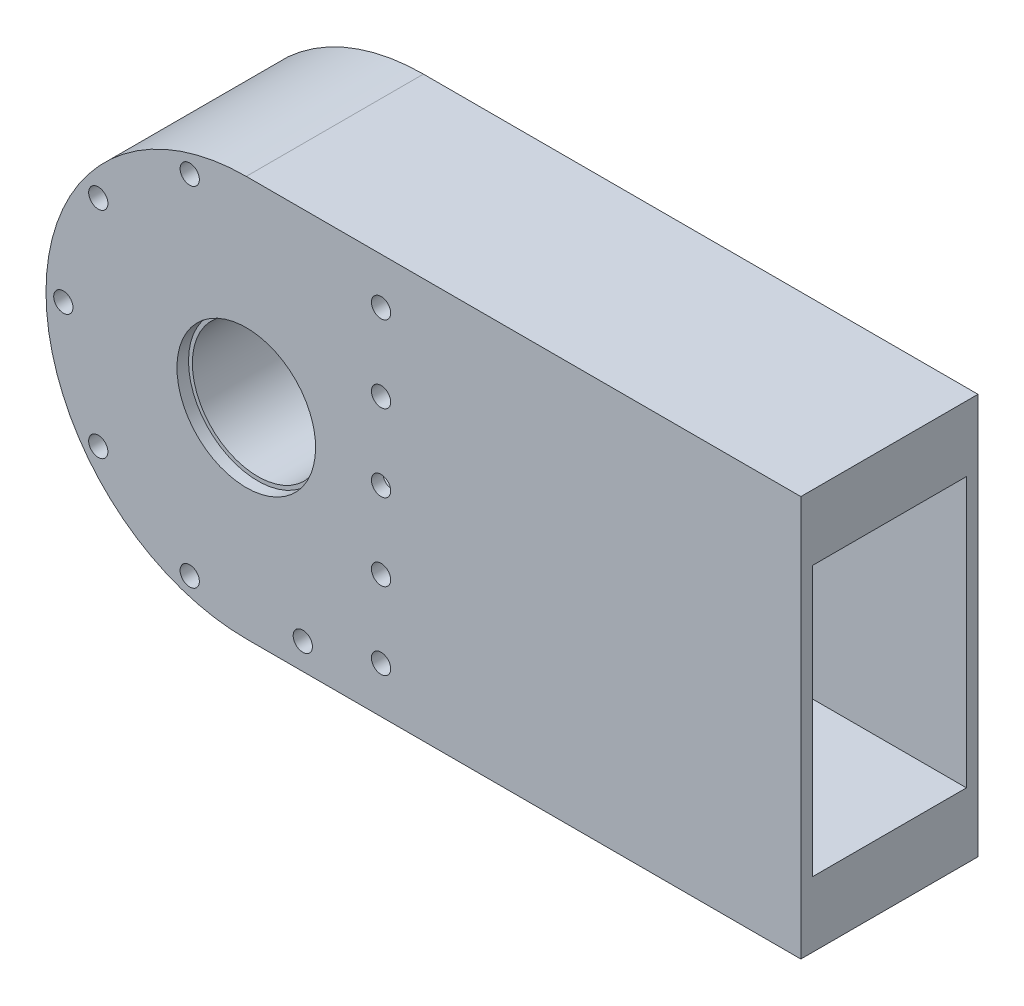
SolidWorks part; units mm, degrees
ref_plane "Alzado" through (0, 0, 0) normal (0, 0, 1) x (1, 0, 0)
ref_plane "Planta" through (0, 0, 0) normal (0, 1, 0) x (1, 0, 0)
ref_plane "Vista lateral" through (0, 0, 0) normal (1, 0, 0) x (0, 0, -1)
sketch "Croquis2" plane through (0, 0, 0) normal (0, 0, 1) x (1, 0, 0)
  line L0 (0, 52) -> (144, 52)
  line L1 (0, -52) -> (144, -52)
  line L2 (144, 52) -> (144, -52)
  line L3 (40, 35) -> (40, -35)
  line L4 (40, -35) -> (144, -35)
  line L5 (40, 35) -> (144, 35)
  line L6 (40, 5) -> (16.2481, 5)
  line L7 (40, -5) -> (16.2481, -5)
  line L8 (28.124, 5) -> (28.124, -5) construction
  arc A0 (0, 52) -> (0, -52) centre (0, 0) ccw
  circle A1 centre (0, 0) radius 17
  point P9 (40, 0)
  dimension "D1" = 104
  dimension "D3" = 34
  dimension "D2" = 144
  dimension "D4" = 70
  dimension "D5" = 40
  dimension "D6" = 10
extrude "Saliente-Extruir1" add sketch "Croquis2" along normal blind 40 contours A1 L6 L3 L5 L2 L0 A0 L1 L4 L7
sketch "Croquis4" plane through (0, 0, 40) normal (0, 0, 1) x (1, 0, 0)
  line L0 (144, 52) -> (144, -52)
  line L10 (16.2481, 5) -> (40, 5)
  line L11 (40, 5) -> (40, 35)
  line L12 (40, 35) -> (144, 35)
  line L13 (144, 35) -> (144, 52)
  line L14 (144, 52) -> (0, 52)
  line L15 (0, -52) -> (144, -52)
  line L16 (144, -52) -> (144, -35)
  line L17 (144, -35) -> (40, -35)
  line L18 (40, -35) -> (40, -5)
  line L19 (40, -5) -> (16.2481, -5)
  line L24 (144, 52) -> (0, 52)
  line L25 (0, -52) -> (144, -52)
  circle A1 centre (0, 0) radius 18
  arc A2 (16.2481, 5) -> (16.2481, -5) centre (0, 0) ccw
  arc A3 (0, 52) -> (0, -52) centre (0, 0) ccw
  arc A5 (0, 52) -> (0, -52) centre (0, 0) ccw
  dimension "D2" = 36
  dimension "D1" = 0
extrude "Saliente-Extruir2" add sketch "Croquis4" along normal blind 3
sketch "Croquis5" plane through (0, 0, 0) normal (0, 0, -1) x (-1, 0, 0)
  line L0 (0, -52) -> (-144, -52)
  line L1 (-144, -52) -> (-144, 52)
  line L2 (-144, 52) -> (0, 52)
  arc A0 (0, -52) -> (0, 52) centre (0, 0) ccw
extrude "Saliente-Extruir3" add sketch "Croquis5" along normal blind 3
sketch "Croquis6" plane through (0, 0, -3) normal (0, 0, -1) x (-1, 0, 0)
  line L0 (0, 0) -> (-144, 0) construction
  line L1 (-144, 52) -> (-144, -52) construction
  line L2 (-72, 0) -> (-72, 52) construction
  line L3 (0, 52) -> (-144, 52) construction
  circle A0 centre (-135, 42.5) radius 2.5
  circle A1 centre (-9, 42.5) radius 2.5
  circle A2 centre (-9, -42.5) radius 2.5
  circle A3 centre (-135, -42.5) radius 2.5
  circle A4 centre (45, 0) radius 2.5
  dimension "D1" = 5
  dimension "D4" = 5
  dimension "D2" = 135
  dimension "D3" = 42.5
  dimension "D5" = 45
extrude "Cortar-Extruir1" cut sketch "Croquis6" against normal blind 10
sketch "Croquis7" plane through (0, 0, 43) normal (0, 0, 1) x (1, 0, 0)
  line L0 (0, 0) -> (-14.6783, 45.1752) construction
  line L2 (40, -35) -> (144, -35) construction
  line L5 (0, 0) -> (57.5458, 0) construction
  line L9 (40, 35) -> (40, -35) construction
  line L10 (40, 35) -> (144, 35) construction
  line L11 (0, 0) -> (0, 47.5) construction
  line L13 (40, -35) -> (144, -35) construction
  line L14 (40, 35) -> (40, -35) construction
  line L15 (40, 35) -> (144, 35) construction
  circle A0 centre (35, 0) radius 2.5
  circle A1 centre (35, 20) radius 2.5
  circle A5 centre (35, 40) radius 2.5
  circle A6 centre (35, -40) radius 2.5
  circle A7 centre (35, -20) radius 2.5
  circle A8 centre (0, 0) radius 47.5 construction
  circle A9 centre (-14.6783, 45.1752) radius 2.5
  circle A10 centre (0, 47.5) radius 2.5 construction
  circle A11 centre (-27.9198, 38.4283) radius 2.5 construction
  circle A12 centre (-45.1752, 14.6783) radius 2.5 construction
  circle A13 centre (-45.1752, -14.6783) radius 2.5 construction
  circle A14 centre (-27.9198, -38.4283) radius 2.5 construction
  circle A15 centre (0, -47.5) radius 2.5 construction
  circle A16 centre (-38.4283, 27.9198) radius 2.5
  circle A17 centre (-47.5, 0) radius 2.5
  circle A18 centre (-38.4283, -27.9198) radius 2.5
  circle A19 centre (-14.6783, -45.1752) radius 2.5
  circle A20 centre (14.6783, -45.1752) radius 2.5
  point P35 (0, 0)
  point P47 (0, 0)
  dimension "D1" = 5
  dimension "D4" = 95
  dimension "D5" = 5
  dimension "D7" = 5
  dimension "D2" = 35
  dimension "D6" = 18
  dimension "D9" = 6
  dimension "D3" = 3
  dimension "D8" = 6
extrude "Cortar-Extruir2" cut sketch "Croquis7" against normal blind 25
